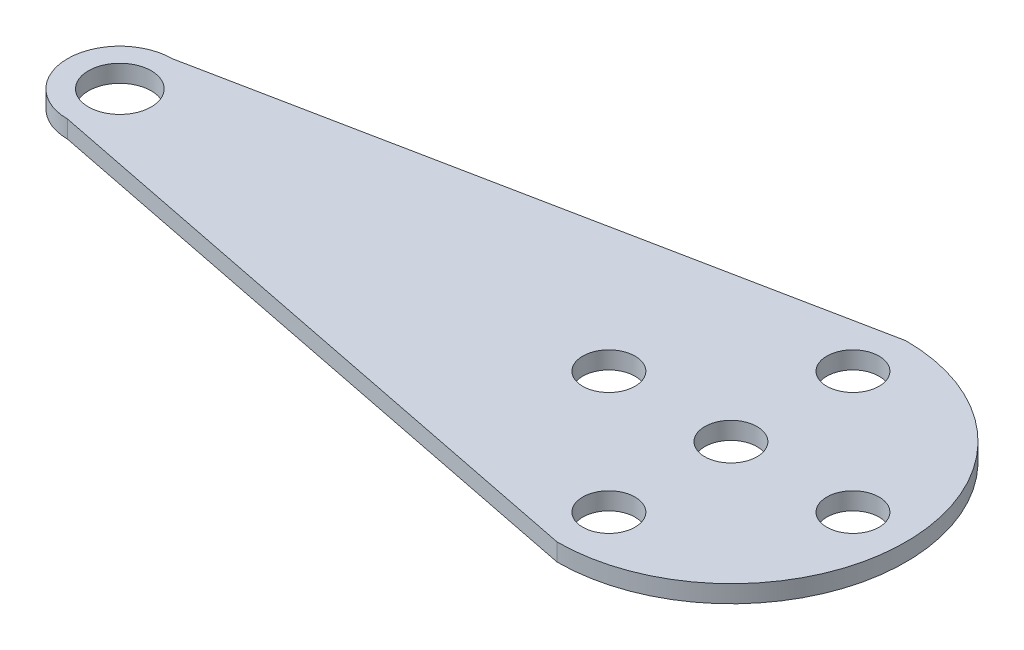
SolidWorks part; units mm, degrees
ref_plane "Płaszczyzna przednia" through (0, 0, 0) normal (0, 0, 1) x (1, 0, 0)
ref_plane "Płaszczyzna górna" through (0, 0, 0) normal (0, 1, 0) x (1, 0, 0)
ref_plane "Płaszczyzna prawa" through (0, 0, 0) normal (1, 0, 0) x (0, 0, -1)
sketch "Sketch1" plane through (0, 0, 0) normal (0, 1, 0) x (1, 0, 0)
  line L8 (0.0031, 0.031) -> (0.0031, 10.031)
  line L9 (0.0031, 0.031) -> (0.0031, -9.969)
  line L10 (0.0031, 10.031) -> (-35.05, 3)
  line L11 (0.0031, 0.031) -> (-35.05, 0)
  line L12 (0.0031, -9.969) -> (-35.05, -3)
  line L13 (-35.05, 3) -> (-35.05, -3)
  circle A0 centre (0.0031, 0.031) radius 10
  circle A1 centre (-35.05, 0) radius 3
  point P0 (0, 0)
  dimension "D1" = 35.05
extrude "Boss-Extrude1" add sketch "Sketch1" along normal blind 1 contours L9 A0 L8 | A1 L11 A0 L10 | L10 A0 L11 L8 | L11 A0 L12 L9 | A1 L12 A0 L11 | L13 A1 L11 | L11 A1 L13 | L13 A1
sketch "Sketch5" plane through (0, 0, 0) normal (0, -1, 0) x (1, 0, 0)
  line L0 (0, 0) -> (0, 7)
  line L1 (0, 0) -> (-35.05, 0)
  circle A0 centre (0, 0) radius 1.5
  circle A1 centre (0, 7) radius 1.5
  circle A2 centre (7, 0) radius 1.5
  circle A3 centre (0, -7) radius 1.5
  circle A4 centre (-7, 0) radius 1.5
  circle A5 centre (-35.05, 0) radius 1.8
  point P13 (0, 0)
  dimension "D1" = 4
extrude "Cut-Extrude4" cut sketch "Sketch5" against normal blind 11
